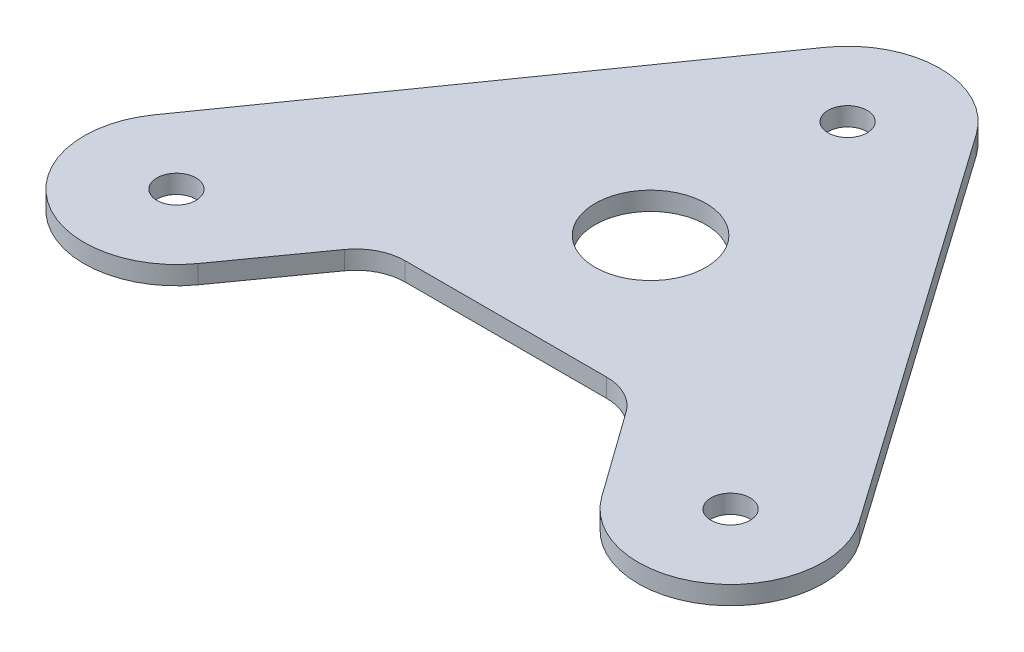
SolidWorks part; units mm, degrees
ref_plane "Front" through (0, 0, 0) normal (0, 0, 1) x (1, 0, 0)
ref_plane "Top" through (0, 0, 0) normal (0, 1, 0) x (1, 0, 0)
ref_plane "Right" through (0, 0, 0) normal (1, 0, 0) x (0, 0, -1)
sketch "Sketch1" plane through (0, 0, 0) normal (0, 1, 0) x (1, 0, 0)
  line L18 (-32.7997, -60.4256) -> (-22.8712, -46.5449)
  line L19 (-57.2704, -43.0714) -> (-12.2704, 20.9286)
  line L20 (57.2704, -43.0714) -> (12.2704, 20.9286)
  line L21 (16.3643, -43.199) -> (-16.3643, -43.199)
  line L22 (32.7997, -60.4256) -> (22.8712, -46.5449)
  circle A4 centre (0, -19.699) radius 9
  arc A5 (-16.3643, -43.199) -> (-23.9492, -48.6555) centre (-16.3643, -51.199) ccw
  arc A6 (23.9492, -48.6555) -> (16.3643, -43.199) centre (16.3643, -51.199) ccw
  circle A7 centre (0, 12.301) radius 15
  circle A8 centre (45, -51.699) radius 15
  circle A9 centre (-45, -51.699) radius 15
  circle A10 centre (-45, -51.699) radius 3.175
  circle A11 centre (45, -51.699) radius 3.175
  circle A12 centre (0, 12.301) radius 3.175
  dimension "D8" = 18
  dimension "D17" = 23.5
  dimension "D7" = 30
  dimension "D9" = 30
  dimension "D10" = 30
  dimension "D11" = 6.35
  dimension "D12" = 6.35
  dimension "D13" = 6.35
  dimension "D2" = 90
  dimension "D3" = 64
  dimension "D4" = 64
  dimension "D5" = 45
  dimension "D6" = 32
extrude "Boss-Extrude1" add sketch "Sketch1" along normal blind 3 contours A9 | A9 L18 A5 L21 A6 L22 A8 L20 A7 L19 A4 | A7 | A8
